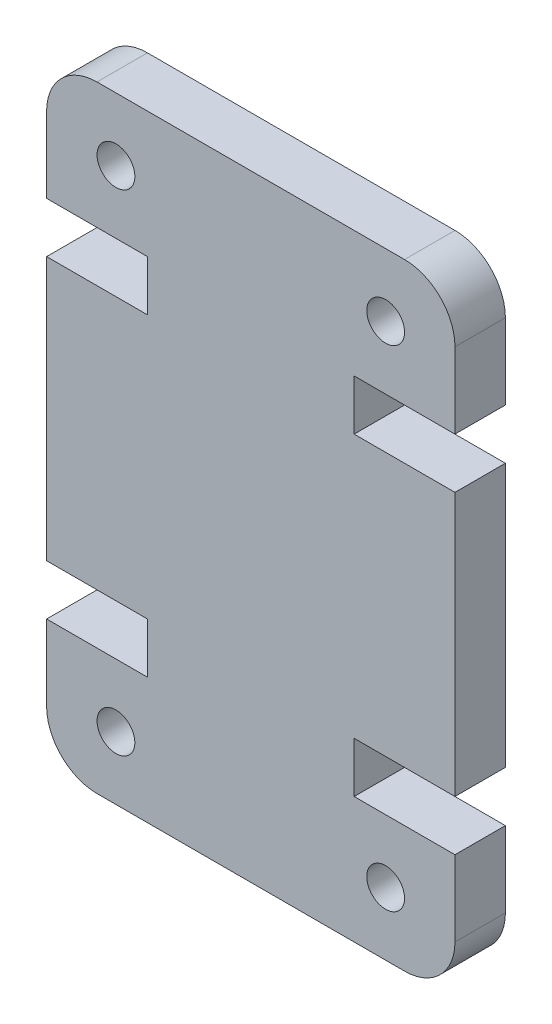
SolidWorks part; units mm, degrees
ref_plane "Front Plane" through (0, 0, 0) normal (0, 0, 1) x (1, 0, 0)
ref_plane "Top Plane" through (0, 0, 0) normal (0, 1, 0) x (1, 0, 0)
ref_plane "Right Plane" through (0, 0, 0) normal (1, 0, 0) x (0, 0, -1)
sketch "Sketch1" plane through (0, 0, 0) normal (0, 0, 1) x (1, 0, 0)
  line L0 (0, 17.45) -> (0, 7)
  line L1 (16.2, 17.45) -> (16.2, 7)
  line L2 (2, 24.45) -> (14.2, 24.45)
  line L3 (2, 0) -> (14.2, 0)
  line L4 (4, 19.45) -> (4, 17.45)
  line L5 (16.2, 19.45) -> (12.2, 19.45)
  line L6 (0, 19.45) -> (4, 19.45)
  line L7 (4, 17.45) -> (0, 17.45)
  line L8 (12.2, 19.45) -> (12.2, 17.45)
  line L9 (12.2, 17.45) -> (16.2, 17.45)
  line L10 (4, 7) -> (4, 5)
  line L11 (12.2, 7) -> (12.2, 5)
  line L12 (0, 7) -> (4, 7)
  line L13 (4, 5) -> (0, 5)
  line L14 (12.2, 5) -> (16.2, 5)
  line L15 (16.2, 7) -> (12.2, 7)
  line L16 (16.2, 22.45) -> (16.2, 19.45)
  line L17 (16.2, 5) -> (16.2, 2)
  line L18 (0, 22.45) -> (0, 19.45)
  line L19 (0, 5) -> (0, 2)
  arc A0 (2, 24.45) -> (0, 22.45) centre (2, 22.45) ccw
  arc A1 (16.2, 22.45) -> (14.2, 24.45) centre (14.2, 22.45) ccw
  arc A2 (14.2, 0) -> (16.2, 2) centre (14.2, 2) ccw
  arc A3 (0, 2) -> (2, 0) centre (2, 2) ccw
  circle A4 centre (13.45, 2.5) radius 0.75
  circle A5 centre (2.75, 2.5) radius 0.75
  circle A6 centre (13.45, 21.95) radius 0.75
  circle A7 centre (2.75, 21.95) radius 0.75
extrude "Boss-Extrude1" add sketch "Sketch1" along normal blind 2
